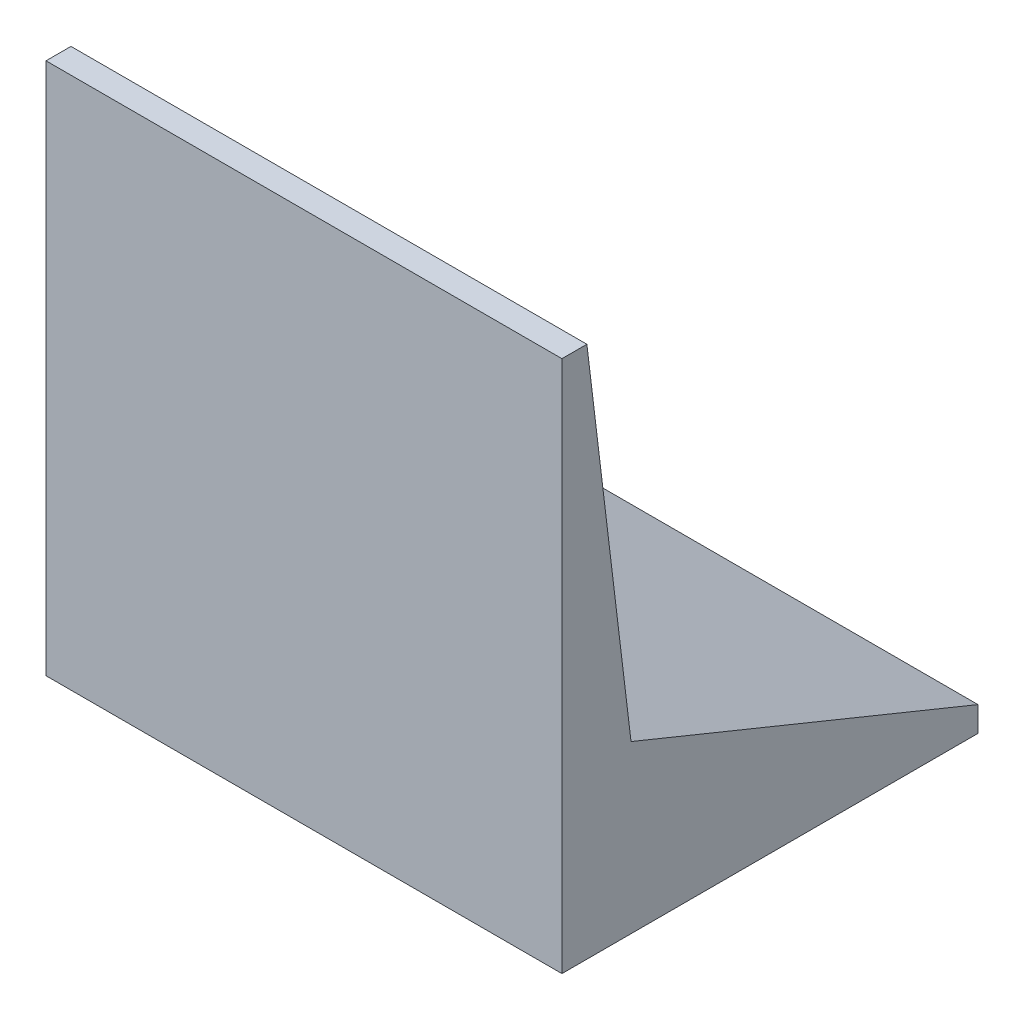
SolidWorks part; units mm, degrees
ref_plane "Front Plane" through (0, 0, 0) normal (0, 0, 1) x (1, 0, 0)
ref_plane "Top Plane" through (0, 0, 0) normal (0, 1, 0) x (1, 0, 0)
ref_plane "Right Plane" through (0, 0, 0) normal (1, 0, 0) x (0, 0, -1)
sketch "Sketch1" plane through (0, 0, 0) normal (1, 0, 0) x (0, 0, -1)
  line L0 (0, 0) -> (-250, 0)
  line L1 (-250, 0) -> (-250, 320)
  line L2 (-250, 320) -> (-235, 320)
  line L3 (-235, 320) -> (-208.4787, 100)
  line L4 (-208.4787, 100) -> (0, 15)
  line L5 (0, 15) -> (0, 0)
  point P3 (0, 22.3562)
  dimension "D1" = 320
  dimension "D2" = 250
  dimension "D3" = 15
  dimension "D4" = 220
  dimension "D5" = 15
extrude "Boss-Extrude1" add sketch "Sketch1" along normal blind 310
